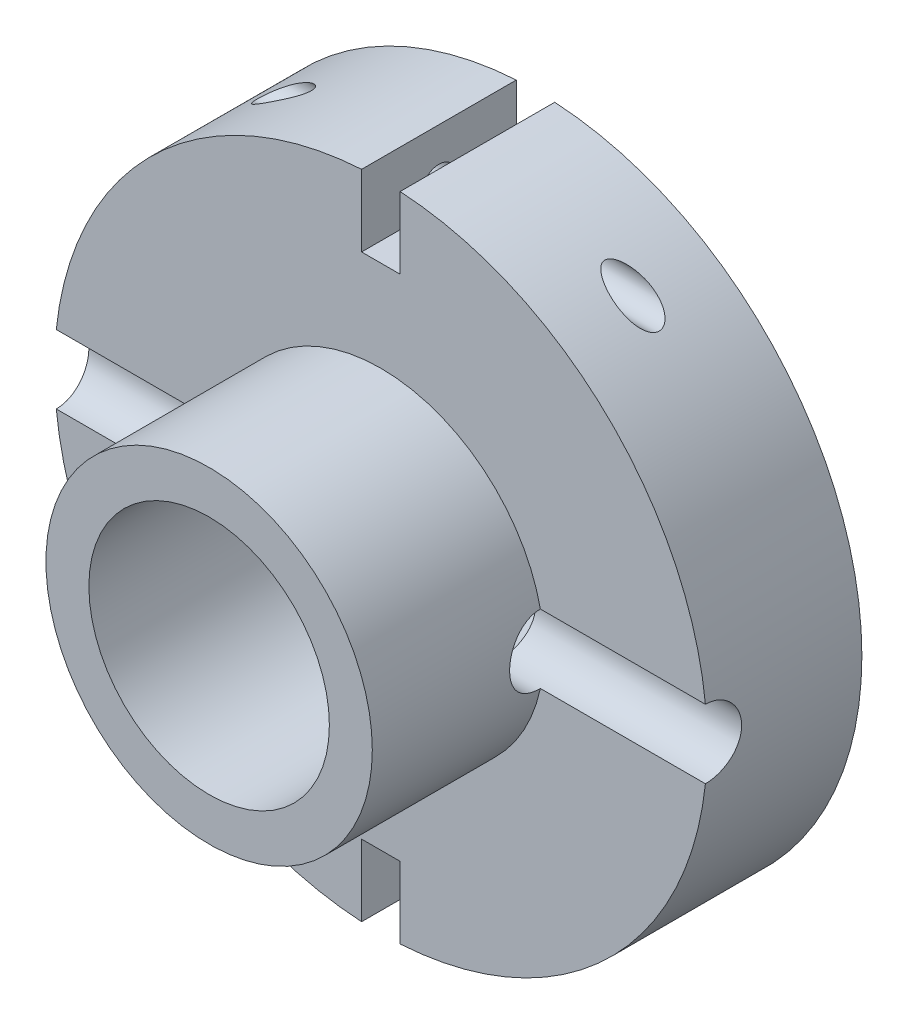
SolidWorks part; units mm, degrees
ref_plane "Plan de face" through (0, 0, 0) normal (0, 0, 1) x (1, 0, 0)
ref_plane "Plan de dessus" through (0, 0, 0) normal (0, 1, 0) x (1, 0, 0)
ref_plane "Plan de droite" through (0, 0, 0) normal (1, 0, 0) x (0, 0, -1)
sketch "Esquisse1" plane through (0, 0, 0) normal (0, 0, 1) x (1, 0, 0)
  circle A0 centre (0, 0) radius 50
  circle A1 centre (0, 0) radius 67.85
  dimension "D1" = 100
  dimension "D2" = 135.7
extrude "Boss.-Extru.1" add sketch "Esquisse1" against normal blind 71.4
sketch "Esquisse3" plane through (0, 0, -71.4) normal (0, 0, -1) x (-1, 0, 0)
  circle A0 centre (0, 0) radius 50
  circle A1 centre (0, 0) radius 135.7
  dimension "D1" = 100
  dimension "D2" = 271.4
extrude "Boss.-Extru.2" add sketch "Esquisse3" along normal blind 64.3
sketch "Esquisse4" plane through (0, 0, 0) normal (1, 0, 0) x (0, 0, -1)
  line L0 (71.4, 135.7) -> (71.4, -135.7) construction
  line L1 (0, 0) -> (71.4, 0) construction
  circle A0 centre (71.4, 0) radius 14.3
  dimension "D1" = 28.6
extrude "Enlèv. mat.-Extru.1" cut sketch "Esquisse4" against normal through all and the other way through all
sketch "Esquisse6" plane through (0, 0, -135.7) normal (0, 0, -1) x (-1, 0, 0)
  line L0 (0, 0) -> (0, 157.3265) construction
  line L1 (-8, 105.7) -> (8, 105.7)
  line L2 (-8, 105.7) -> (-8, 135.464)
  line L3 (8, 105.7) -> (8, 135.464)
  line L4 (74.635, 0) -> (-74.635, 0) construction
  line L5 (8, -105.7) -> (8, -135.464)
  line L6 (-8, -105.7) -> (8, -105.7)
  line L7 (-8, -105.7) -> (-8, -135.464)
  arc A0 (8, -135.464) -> (-8, -135.464) centre (0, 0) cw
  arc A1 (8, 135.464) -> (-8, 135.464) centre (0, 0) ccw
  point P5 (0, 105.7)
  point P6 (0, 135.7)
  dimension "D2" = 271.4
  dimension "D1" = 16
  dimension "D3" = 30
extrude "Enlèv. mat.-Extru.2" cut sketch "Esquisse6" against normal through all
sketch "Esquisse7" plane through (0, 0, 0) normal (1, 0, 0) x (0, 0, -1)
  line L0 (103.55, 135.464) -> (103.55, 114.064) construction
  line L1 (71.4, 135.464) -> (135.7, 135.464) construction
  line L2 (74.635, 0) -> (-74.635, 0) construction
  circle A0 centre (103.55, 114.064) radius 7.15
  circle A1 centre (103.55, -114.064) radius 7.15
  dimension "D2" = 14.3
  dimension "D1" = 21.4
extrude "Enlèv. mat.-Extru.3" cut sketch "Esquisse7" against normal through all and the other way through all
